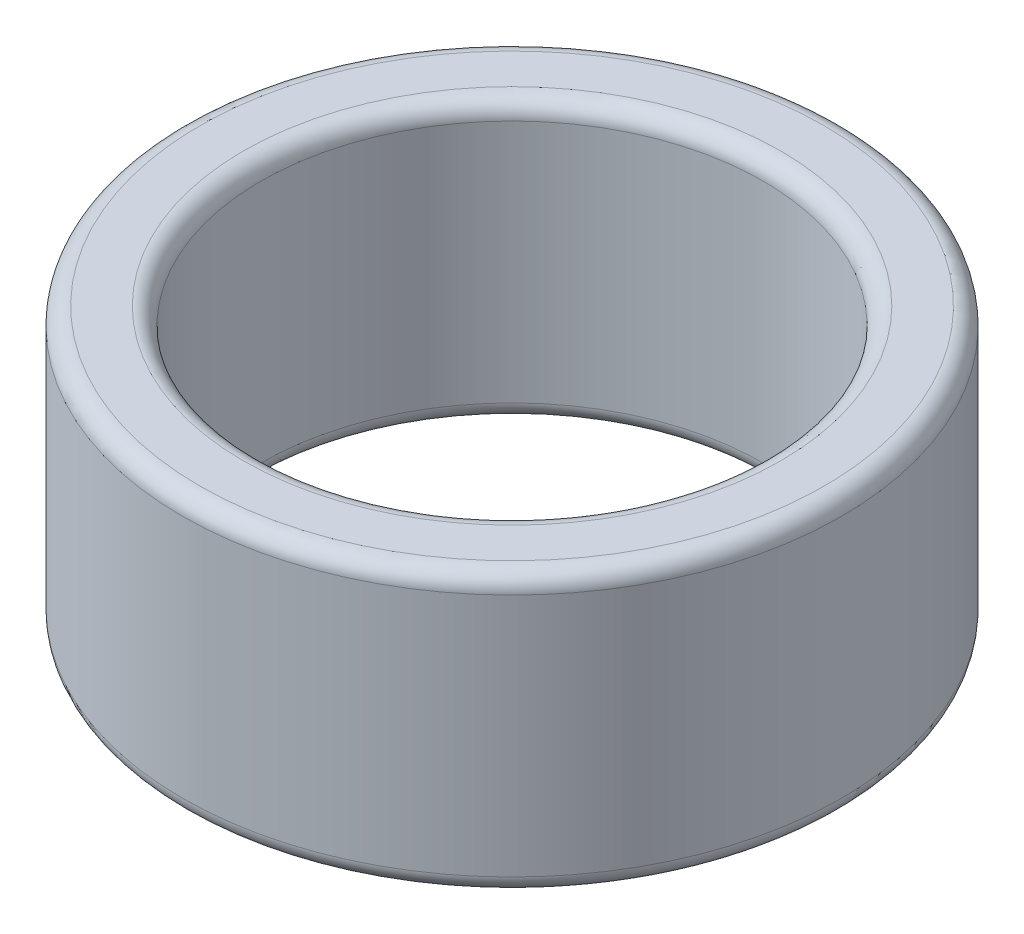
SolidWorks part; units mm, degrees
ref_plane "Front Plane" through (0, 0, 0) normal (0, 0, 1) x (1, 0, 0)
ref_plane "Top Plane" through (0, 0, 0) normal (0, 1, 0) x (1, 0, 0)
ref_plane "Right Plane" through (0, 0, 0) normal (1, 0, 0) x (0, 0, -1)
sketch "Sketch1" plane through (0, 0, 0) normal (0, 1, 0) x (1, 0, 0)
  circle A0 centre (0, 0) radius 9.45
  circle A1 centre (0, 0) radius 7.2
  dimension "D1" = 18.9
  dimension "D2" = 14.4
extrude "Boss-Extrude1" add sketch "Sketch1" along normal blind 8
ref_plane "Plane1" through (0, 10, 0) normal (0, 1, 0) x (1, 0, 0)
fillet "Fillet1" radius 0.5 4 edges at (0, 0, 9.45) (0, 8, 9.45) (0, 0, 7.2) (0, 8, 7.2)
